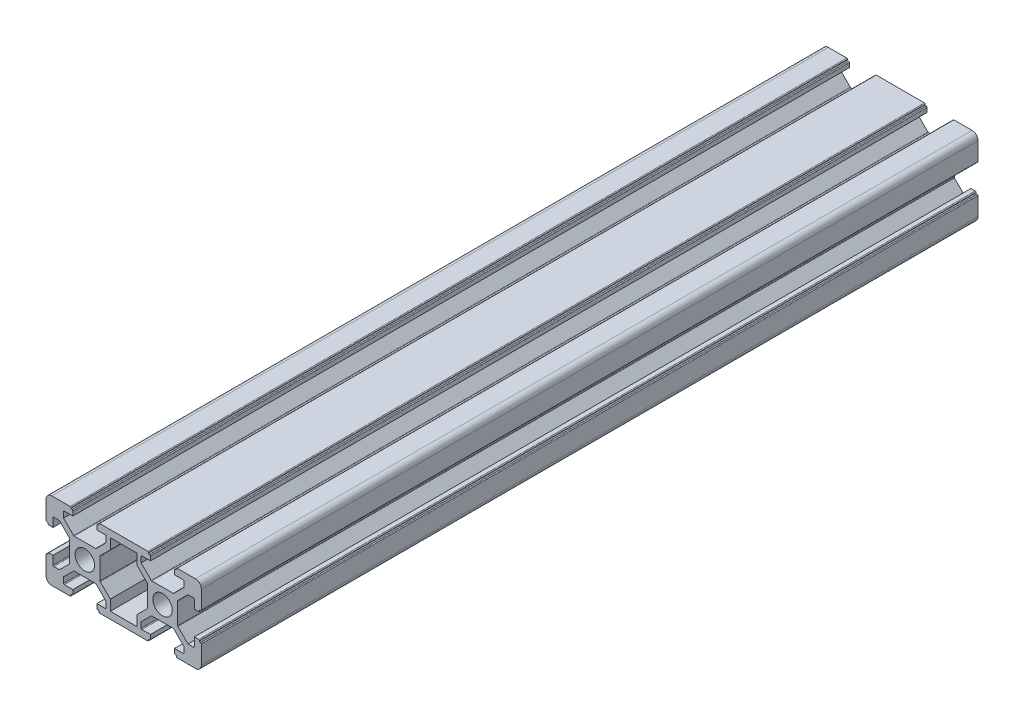
SolidWorks part; units mm, degrees
ref_plane "前视基准面" through (0, 0, 0) normal (0, 0, 1) x (1, 0, 0)
ref_plane "上视基准面" through (0, 0, 0) normal (0, 1, 0) x (1, 0, 0)
ref_plane "右视基准面" through (0, 0, 0) normal (1, 0, 0) x (0, 0, -1)
sketch "Sketch1" plane through (0, 0, 0) normal (0, 0, 1) x (1, 0, 0)
  line L0 (-8.5, 10) -> (-3.8, 10)
  line L3 (-8.5, -10) -> (-3.8, -10)
  line L5 (-10, 8.5) -> (-10, 3.8)
  line L6 (-2.7565, 3.9) -> (2.7565, 3.9)
  line L9 (-2.7565, -3.9) -> (2.7565, -3.9)
  line L10 (3.9, 2.7565) -> (3.9, -2.7565)
  line L11 (-3.9, 2.7565) -> (-3.9, -2.7565)
  line L12 (-3.9586, -2.8979) -> (-6.5607, -5.5)
  line L13 (3.6, 9.7) -> (3.6, 9.8)
  line L14 (3.1, -8.2) -> (5.3, -8.2)
  line L15 (-2.8979, -3.9586) -> (-5.5, -6.5607)
  line L16 (-3.1, -8.2) -> (-3.1, -9.3)
  line L17 (3.1, -8.2) -> (3.1, -9.3)
  line L18 (-5.5, -6.5607) -> (-5.5, -8)
  line L19 (5.5, -6.5607) -> (5.5, -8)
  line L20 (-5.3, -8.2) -> (-3.1, -8.2)
  line L21 (-3.4, -9.5) -> (-3.3, -9.5)
  line L22 (3.8, -10) -> (8.5, -10)
  line L23 (3.3, -9.5) -> (3.4, -9.5)
  line L24 (-3.6, -9.7) -> (-3.6, -9.8)
  line L25 (3.6, -9.7) -> (3.6, -9.8)
  line L26 (-6.5607, -5.5) -> (-8, -5.5)
  line L27 (-9.7, -3.6) -> (-9.8, -3.6)
  line L28 (-9.5, -3.4) -> (-9.5, -3.3)
  line L29 (-8.2, -3.1) -> (-9.3, -3.1)
  line L30 (-8.2, -5.3) -> (-8.2, -3.1)
  line L31 (-10, -3.8) -> (-10, -8.5)
  line L33 (3.8, 10) -> (8.5, 10)
  line L34 (2.8979, -3.9586) -> (5.5, -6.5607)
  line L40 (3.9586, -2.8979) -> (6.5607, -5.5)
  line L41 (3.3, 9.5) -> (3.4, 9.5)
  line L42 (30, 8.5) -> (30, 3.8)
  line L43 (3.1, 8.2) -> (3.1, 9.3)
  line L44 (3.1, 8.2) -> (5.3, 8.2)
  line L45 (5.5, 6.5607) -> (5.5, 8)
  line L46 (2.8979, 3.9586) -> (5.5, 6.5607)
  line L52 (3.9586, 2.8979) -> (6.5607, 5.5)
  line L53 (-3.6, 9.7) -> (-3.6, 9.8)
  line L54 (-3.4, 9.5) -> (-3.3, 9.5)
  line L55 (-3.1, 8.2) -> (-3.1, 9.3)
  line L56 (-5.3, 8.2) -> (-3.1, 8.2)
  line L57 (-5.5, 6.5607) -> (-5.5, 8)
  line L58 (-2.8979, 3.9586) -> (-5.5, 6.5607)
  line L59 (-9.5, 3.4) -> (-9.5, 3.3)
  line L60 (-9.7, 3.6) -> (-9.8, 3.6)
  line L61 (-8.2, 3.1) -> (-9.3, 3.1)
  line L62 (-8.2, 5.3) -> (-8.2, 3.1)
  line L63 (-6.5607, 5.5) -> (-8, 5.5)
  line L64 (-3.9586, 2.8979) -> (-6.5607, 5.5)
  line L65 (29.7, 3.6) -> (29.8, 3.6)
  line L66 (29.5, 3.4) -> (29.5, 3.3)
  line L67 (28.2, 3.1) -> (29.3, 3.1)
  line L68 (28.2, 5.3) -> (28.2, 3.1)
  line L69 (26.5607, 5.5) -> (28, 5.5)
  line L70 (23.9586, 2.8979) -> (26.5607, 5.5)
  line L71 (23.9, 2.7565) -> (23.9, -2.7565)
  line L72 (23.9586, -2.8979) -> (26.5607, -5.5)
  line L73 (26.5607, -5.5) -> (28, -5.5)
  line L74 (28.2, -5.3) -> (28.2, -3.1)
  line L75 (28.2, -3.1) -> (29.3, -3.1)
  line L76 (29.5, -3.4) -> (29.5, -3.3)
  line L77 (29.7, -3.6) -> (29.8, -3.6)
  line L78 (30, -3.8) -> (30, -8.5)
  line L79 (28.5, -10) -> (23.8, -10)
  line L80 (23.6, -9.7) -> (23.6, -9.8)
  line L81 (23.4, -9.5) -> (23.3, -9.5)
  line L82 (23.1, -8.2) -> (23.1, -9.3)
  line L83 (25.3, -8.2) -> (23.1, -8.2)
  line L84 (25.5, -6.5607) -> (25.5, -8)
  line L85 (22.8979, -3.9586) -> (25.5, -6.5607)
  line L86 (22.7565, -3.9) -> (17.2435, -3.9)
  line L87 (17.1021, -3.9586) -> (14.5, -6.5607)
  line L88 (14.5, -6.5607) -> (14.5, -8)
  line L89 (16.9, -8.2) -> (14.7, -8.2)
  line L90 (16.9, -8.2) -> (16.9, -9.3)
  line L91 (16.7, -9.5) -> (16.6, -9.5)
  line L92 (16.4, -9.7) -> (16.4, -9.8)
  line L93 (16.2, -10) -> (11.5, -10)
  line L94 (13.4393, 5.5) -> (13.4393, 8.2)
  line L96 (6.5607, 5.5) -> (6.5607, 8.2)
  line L97 (6.5607, 8.2) -> (13.4393, 8.2)
  line L99 (16.0414, -2.8979) -> (13.4393, -5.5)
  line L100 (16.1, 2.7565) -> (16.1, -2.7565)
  line L101 (16.0414, 2.8979) -> (13.4393, 5.5)
  line L107 (16.2, 10) -> (11.5, 10)
  line L108 (16.4, 9.7) -> (16.4, 9.8)
  line L109 (16.7, 9.5) -> (16.6, 9.5)
  line L110 (16.9, 8.2) -> (16.9, 9.3)
  line L111 (16.9, 8.2) -> (14.7, 8.2)
  line L112 (14.5, 6.5607) -> (14.5, 8)
  line L113 (17.1021, 3.9586) -> (14.5, 6.5607)
  line L114 (22.7565, 3.9) -> (17.2435, 3.9)
  line L115 (22.8979, 3.9586) -> (25.5, 6.5607)
  line L116 (25.5, 6.5607) -> (25.5, 8)
  line L117 (25.3, 8.2) -> (23.1, 8.2)
  line L118 (23.1, 8.2) -> (23.1, 9.3)
  line L119 (23.4, 9.5) -> (23.3, 9.5)
  line L120 (23.6, 9.7) -> (23.6, 9.8)
  line L121 (28.5, 10) -> (23.8, 10)
  line L122 (13.4393, -5.5) -> (13.4393, -8.2)
  line L124 (6.5607, -5.5) -> (6.5607, -8.2)
  line L125 (6.5607, -8.2) -> (13.4393, -8.2)
  line L127 (8.5, 10) -> (11.5, 10)
  line L128 (8.5, -10) -> (11.5, -10)
  arc A3 (-8.5, -10) -> (-10, -8.5) centre (-8.5, -8.5) cw
  arc A4 (-10, 8.5) -> (-8.5, 10) centre (-8.5, 8.5) cw
  arc A5 (3.4, -9.5) -> (3.6, -9.7) centre (3.4, -9.7) cw
  arc A6 (3.8, -10) -> (3.6, -9.8) centre (3.8, -9.8) cw
  arc A7 (3.3, -9.5) -> (3.1, -9.3) centre (3.3, -9.3) cw
  arc A8 (5.3, -8.2) -> (5.5, -8) centre (5.3, -8) ccw
  arc A9 (-3.9, -2.7565) -> (-3.9586, -2.8979) centre (-4.1, -2.7565) cw
  arc A10 (-3.9, 2.7565) -> (-3.9586, 2.8979) centre (-4.1, 2.7565) ccw
  arc A11 (-2.7565, 3.9) -> (-2.8979, 3.9586) centre (-2.7565, 4.1) cw
  arc A12 (2.7565, 3.9) -> (2.8979, 3.9586) centre (2.7565, 4.1) ccw
  arc A13 (3.9586, 2.8979) -> (3.9, 2.7565) centre (4.1, 2.7565) ccw
  arc A14 (3.9, -2.7565) -> (3.9586, -2.8979) centre (4.1, -2.7565) ccw
  arc A15 (-2.8979, -3.9586) -> (-2.7565, -3.9) centre (-2.7565, -4.1) cw
  arc A16 (2.7565, -3.9) -> (2.8979, -3.9586) centre (2.7565, -4.1) cw
  arc A17 (-3.6, -9.8) -> (-3.8, -10) centre (-3.8, -9.8) cw
  arc A18 (-3.3, -9.5) -> (-3.1, -9.3) centre (-3.3, -9.3) ccw
  arc A19 (-3.6, -9.7) -> (-3.4, -9.5) centre (-3.4, -9.7) cw
  arc A20 (-8.2, 5.3) -> (-8, 5.5) centre (-8, 5.3) cw
  arc A23 (-8.2, -5.3) -> (-8, -5.5) centre (-8, -5.3) ccw
  arc A24 (-5.3, -8.2) -> (-5.5, -8) centre (-5.3, -8) cw
  arc A31 (3.1, 9.3) -> (3.3, 9.5) centre (3.3, 9.3) cw
  arc A32 (3.6, 9.8) -> (3.8, 10) centre (3.8, 9.8) cw
  arc A33 (3.6, 9.7) -> (3.4, 9.5) centre (3.4, 9.7) cw
  arc A34 (-3.8, 10) -> (-3.6, 9.8) centre (-3.8, 9.8) cw
  arc A35 (-3.3, 9.5) -> (-3.1, 9.3) centre (-3.3, 9.3) cw
  arc A36 (-3.4, 9.5) -> (-3.6, 9.7) centre (-3.4, 9.7) cw
  arc A37 (5.5, 8) -> (5.3, 8.2) centre (5.3, 8) ccw
  arc A38 (-5.5, 8) -> (-5.3, 8.2) centre (-5.3, 8) cw
  arc A39 (-10, 3.8) -> (-9.8, 3.6) centre (-9.8, 3.8) ccw
  arc A40 (-9.5, 3.3) -> (-9.3, 3.1) centre (-9.3, 3.3) ccw
  arc A41 (-9.7, 3.6) -> (-9.5, 3.4) centre (-9.7, 3.4) cw
  arc A42 (-10, -3.8) -> (-9.8, -3.6) centre (-9.8, -3.8) cw
  arc A43 (-9.5, -3.3) -> (-9.3, -3.1) centre (-9.3, -3.3) cw
  arc A44 (-9.5, -3.4) -> (-9.7, -3.6) centre (-9.7, -3.4) cw
  arc A45 (30, 8.5) -> (28.5, 10) centre (28.5, 8.5) ccw
  arc A46 (30, 3.8) -> (29.8, 3.6) centre (29.8, 3.8) cw
  arc A47 (29.7, 3.6) -> (29.5, 3.4) centre (29.7, 3.4) ccw
  arc A48 (29.5, 3.3) -> (29.3, 3.1) centre (29.3, 3.3) cw
  arc A49 (28.2, 5.3) -> (28, 5.5) centre (28, 5.3) ccw
  arc A50 (23.9, 2.7565) -> (23.9586, 2.8979) centre (24.1, 2.7565) cw
  arc A51 (23.9, -2.7565) -> (23.9586, -2.8979) centre (24.1, -2.7565) ccw
  arc A52 (28.2, -5.3) -> (28, -5.5) centre (28, -5.3) cw
  arc A53 (29.5, -3.3) -> (29.3, -3.1) centre (29.3, -3.3) ccw
  arc A54 (29.5, -3.4) -> (29.7, -3.6) centre (29.7, -3.4) ccw
  arc A55 (30, -3.8) -> (29.8, -3.6) centre (29.8, -3.8) ccw
  arc A56 (28.5, -10) -> (30, -8.5) centre (28.5, -8.5) ccw
  arc A57 (23.6, -9.8) -> (23.8, -10) centre (23.8, -9.8) ccw
  arc A58 (23.6, -9.7) -> (23.4, -9.5) centre (23.4, -9.7) ccw
  arc A59 (23.3, -9.5) -> (23.1, -9.3) centre (23.3, -9.3) cw
  arc A60 (25.3, -8.2) -> (25.5, -8) centre (25.3, -8) ccw
  arc A61 (22.8979, -3.9586) -> (22.7565, -3.9) centre (22.7565, -4.1) ccw
  arc A62 (17.2435, -3.9) -> (17.1021, -3.9586) centre (17.2435, -4.1) ccw
  arc A63 (14.7, -8.2) -> (14.5, -8) centre (14.7, -8) cw
  arc A64 (16.7, -9.5) -> (16.9, -9.3) centre (16.7, -9.3) ccw
  arc A65 (16.6, -9.5) -> (16.4, -9.7) centre (16.6, -9.7) ccw
  arc A66 (16.2, -10) -> (16.4, -9.8) centre (16.2, -9.8) ccw
  arc A72 (16.1, -2.7565) -> (16.0414, -2.8979) centre (15.9, -2.7565) cw
  arc A73 (16.0414, 2.8979) -> (16.1, 2.7565) centre (15.9, 2.7565) cw
  arc A79 (16.4, 9.8) -> (16.2, 10) centre (16.2, 9.8) ccw
  arc A80 (16.4, 9.7) -> (16.6, 9.5) centre (16.6, 9.7) ccw
  arc A81 (16.9, 9.3) -> (16.7, 9.5) centre (16.7, 9.3) ccw
  arc A82 (14.5, 8) -> (14.7, 8.2) centre (14.7, 8) cw
  arc A83 (17.2435, 3.9) -> (17.1021, 3.9586) centre (17.2435, 4.1) cw
  arc A84 (22.7565, 3.9) -> (22.8979, 3.9586) centre (22.7565, 4.1) ccw
  arc A85 (25.5, 8) -> (25.3, 8.2) centre (25.3, 8) ccw
  arc A86 (23.3, 9.5) -> (23.1, 9.3) centre (23.3, 9.3) ccw
  arc A87 (23.4, 9.5) -> (23.6, 9.7) centre (23.4, 9.7) ccw
  arc A88 (23.8, 10) -> (23.6, 9.8) centre (23.8, 9.8) ccw
  point P11 (3.9, 3.9)
  point P19 (3.3697, 4.4303)
  point P20 (-10.6428, -10.6428)
  point P25 (-11.1731, -10.1124)
  point P26 (4.4303, 3.3697)
  point P28 (-10.1124, -11.1731)
  dimension "D3" = 0.2
  dimension "D4" = 0.2
  dimension "D5" = 0.2
  dimension "D8" = 0.2
  dimension "D9" = 0.2
  dimension "D10" = 0.2
  dimension "D6" = 1.8
  dimension "D7" = 0.5
extrude "Boss-Extrude1" add sketch "Sketch1" along normal blind 200
ref_plane "hole" through (0, 0, 200) normal (0, 0, 1) x (1, 0, 0)
sketch "Sketch2" plane through (0, 0, 200) normal (0, 0, 1) x (1, 0, 0)
  circle A0 centre (0, 0) radius 2.5
  circle A1 centre (20, 0) radius 2.5
  dimension "D1" = 5
extrude "Cut-Extrude1" cut sketch "Sketch2" against normal through all
sketch "Sketch4" plane through (0, 3.9, 0) normal (0, 1, 0) x (1, 0, 0)
  line L0 (2.7565, -200) -> (-2.7565, -200) construction
  line L1 (10, -200) -> (10, 0) construction
  line L2 (16.2, -200) -> (3.8, -200) construction
  line L3 (16.2, 0) -> (3.8, 0) construction
  circle A0 centre (0, -183.3) radius 1.5
  circle A1 centre (0, -166.6) radius 1.5
  circle A2 centre (20, -166.6) radius 1.5
  circle A3 centre (20, -183.3) radius 1.5
  point P6 (0, -200)
  dimension "D1" = 0
  dimension "D2" = 0
  dimension "D3" = 16.7
  dimension "D4" = 16.7
  dimension "D5" = 3
  dimension "D6" = 3
extrude "Cut-Extrude3" cut sketch "Sketch4" against normal blind 30
